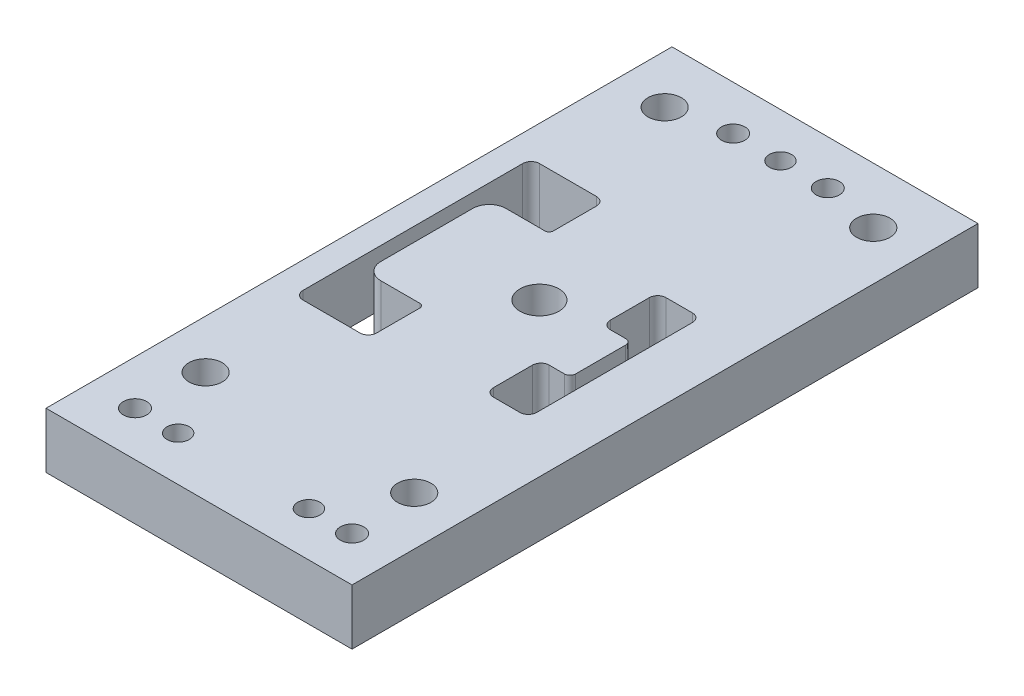
SolidWorks part; units mm, degrees
material "Plain Carbon Steel"
ref_plane "Front Plane" through (0, 0, 0) normal (0, 0, 1) x (1, 0, 0)
ref_plane "Top Plane" through (0, 0, 0) normal (0, 1, 0) x (1, 0, 0)
ref_plane "Right Plane" through (0, 0, 0) normal (1, 0, 0) x (0, 0, -1)
sketch "Sketch1" plane through (0, 0, 0) normal (0, 1, 0) x (1, 0, 0)
  line L1 (-55, -112.5) -> (55, -112.5)
  line L2 (-55, -112.5) -> (-55, 112.5)
  line L3 (-55, 112.5) -> (55, 112.5)
  line L4 (55, -112.5) -> (55, 112.5)
  line L5 (-55, -112.5) -> (55, 112.5) construction
  line L6 (-55, 112.5) -> (55, -112.5) construction
  point P0 (0, 0)
  dimension "D1" = 225
  dimension "D2" = 110
extrude "Boss-Extrude1" add sketch "Sketch1" along normal blind 20
sketch "Sketch2" plane through (0, 20, 0) normal (0, 1, 0) x (1, 0, 0)
  line L0 (-42.5, 37.36) -> (-19, 37.36) construction
  line L1 (-42.5, -17.64) -> (-19, -17.64) construction
  line L8 (-40.5, 26.36) -> (-40.5, -6.64) construction
  line L9 (-42.5, -32.64) -> (-22, -32.64)
  line L11 (-42.5, 52.36) -> (-22, 52.36)
  line L13 (-20.5, 32.36) -> (-34.5, 32.36) construction
  line L14 (-19, 37.36) -> (-19, 33.86) construction
  line L16 (-45.5, 34.36) -> (-45.5, -14.64) construction
  line L18 (-19, -17.64) -> (-19, -14.14) construction
  line L19 (-34.5, -12.64) -> (-20.5, -12.64) construction
  line L20 (-40.5, 26.36) -> (-40.5, -6.64)
  line L21 (-20.5, 32.36) -> (-34.5, 32.36)
  line L22 (-19, 49.36) -> (-19, 33.86)
  line L24 (-45.5, 49.36) -> (-45.5, -29.64)
  line L26 (-19, -29.64) -> (-19, -14.14)
  line L27 (-34.5, -12.64) -> (-20.5, -12.64)
  arc A0 (-22, 52.36) -> (-19, 49.36) centre (-22, 49.36) cw
  arc A1 (-45.5, 49.36) -> (-42.5, 52.36) centre (-42.5, 49.36) cw
  arc A2 (-42.5, -32.64) -> (-45.5, -29.64) centre (-42.5, -29.64) cw
  arc A3 (-22, -32.64) -> (-19, -29.64) centre (-22, -29.64) ccw
  arc A6 (-40.5, -6.64) -> (-34.5, -12.64) centre (-34.5, -6.64) ccw construction
  arc A7 (-34.5, 32.36) -> (-40.5, 26.36) centre (-34.5, 26.36) ccw construction
  arc A8 (-20.5, 32.36) -> (-19, 33.86) centre (-20.5, 33.86) ccw construction
  arc A11 (-19, -14.14) -> (-20.5, -12.64) centre (-20.5, -14.14) ccw construction
  arc A12 (-40.5, -6.64) -> (-34.5, -12.64) centre (-34.5, -6.64) ccw
  arc A13 (-34.5, 32.36) -> (-40.5, 26.36) centre (-34.5, 26.36) ccw
  arc A14 (-20.5, 32.36) -> (-19, 33.86) centre (-20.5, 33.86) ccw
  arc A17 (-19, -14.14) -> (-20.5, -12.64) centre (-20.5, -14.14) ccw
  dimension "D3" = 3
  dimension "D1" = 15
  dimension "D2" = 15
extrude "Cut-Extrude1" cut sketch "Sketch2" against normal up to next
sketch "Sketch3" plane through (0, 20, 0) normal (0, 1, 0) x (1, 0, 0)
  line L0 (22, -8.64) -> (27.5, -8.64) construction
  line L1 (19, -13.64) -> (19, -11.64) construction
  line L3 (34.5, 15.36) -> (34.5, -10.64) construction
  line L5 (19, 18.36) -> (19, 16.36) construction
  line L6 (27.5, 13.36) -> (22, 13.36) construction
  line L7 (29.5, -6.64) -> (29.5, 11.36) construction
  line L8 (22, -8.64) -> (27.5, -8.64)
  line L9 (19, -25.64) -> (19, -11.64)
  line L11 (34.5, 30.36) -> (34.5, -25.64)
  line L13 (19, 30.36) -> (19, 16.36)
  line L14 (27.5, 13.36) -> (22, 13.36)
  line L15 (29.5, -6.64) -> (29.5, 11.36)
  line L16 (22, -28.64) -> (31.5, -28.64)
  line L17 (22, 33.36) -> (31.5, 33.36)
  line L18 (19, 18.36) -> (31.5, 18.36) construction
  line L19 (31.5, -13.64) -> (19, -13.64) construction
  arc A0 (27.5, -8.64) -> (29.5, -6.64) centre (27.5, -6.64) ccw construction
  arc A1 (22, -8.64) -> (19, -11.64) centre (22, -11.64) ccw construction
  arc A4 (19, 16.36) -> (22, 13.36) centre (22, 16.36) ccw construction
  arc A5 (29.5, 11.36) -> (27.5, 13.36) centre (27.5, 11.36) ccw construction
  arc A6 (27.5, -8.64) -> (29.5, -6.64) centre (27.5, -6.64) ccw
  arc A7 (22, -8.64) -> (19, -11.64) centre (22, -11.64) ccw
  arc A10 (19, 16.36) -> (22, 13.36) centre (22, 16.36) ccw
  arc A11 (29.5, 11.36) -> (27.5, 13.36) centre (27.5, 11.36) ccw
  arc A12 (22, 33.36) -> (19, 30.36) centre (22, 30.36) ccw
  arc A13 (31.5, 33.36) -> (34.5, 30.36) centre (31.5, 30.36) cw
  arc A14 (31.5, -28.64) -> (34.5, -25.64) centre (31.5, -25.64) ccw
  arc A15 (22, -28.64) -> (19, -25.64) centre (22, -25.64) cw
  dimension "D3" = 3
  dimension "D1" = 15
  dimension "D2" = 15
extrude "Cut-Extrude2" cut sketch "Sketch3" against normal up to next
sketch "Sketch4" plane through (0, 0, 0) normal (0, -1, 0) x (1, 0, 0)
  circle A0 centre (37.5, 52.64) radius 10.5 construction
  circle A1 centre (12.5, 52.64) radius 10.5 construction
  circle A2 centre (-12.5, 52.64) radius 10.5 construction
  circle A3 centre (-37.5, 52.64) radius 10.5 construction
  circle A4 centre (0, 10.14) radius 10.5 construction
  circle A5 centre (0, -29.86) radius 10.5 construction
  circle A6 centre (37.5, -72.36) radius 10.5 construction
  circle A7 centre (12.5, -72.36) radius 10.5 construction
  circle A8 centre (-12.5, -72.36) radius 10.5 construction
  circle A9 centre (-37.5, -72.36) radius 10.5 construction
  circle A10 centre (37.5, 52.64) radius 10.5
  circle A11 centre (12.5, 52.64) radius 10.5
  circle A12 centre (-12.5, 52.64) radius 10.5
  circle A13 centre (-37.5, 52.64) radius 10.5
  circle A14 centre (0, 10.14) radius 10.5
  circle A15 centre (0, -29.86) radius 10.5
  circle A16 centre (37.5, -72.36) radius 10.5
  circle A17 centre (12.5, -72.36) radius 10.5
  circle A18 centre (-12.5, -72.36) radius 10.5
  circle A19 centre (-37.5, -72.36) radius 10.5
extrude "Cut-Extrude3" cut sketch "Sketch4" against normal blind 14.2
sketch "Sketch5" plane through (0, 20, 0) normal (0, 1, 0) x (1, 0, 0)
  circle A0 centre (-37.5, 92.36) radius 6
  circle A1 centre (37.5, 92.36) radius 6
  circle A2 centre (-37.5, -72.64) radius 6
  circle A3 centre (37.5, -72.64) radius 6
  dimension "D1" = 12
extrude "Cut-Extrude4" cut sketch "Sketch5" against normal up to next
sketch "Sketch6" plane through (0, 20, 0) normal (0, 1, 0) x (1, 0, 0)
  circle A0 centre (0, 9.86) radius 7
  dimension "D1" = 14
extrude "Cut-Extrude5" cut sketch "Sketch6" against normal up to next
hole_wizard "CBORE for M8 Hex Socket Head Cap Screw1" positions "Sketch10" profile "Sketch9" counterbore size "M8" standard "ISO" end condition through all
sketch "Sketch10" plane through (0, 0, 0) normal (0, -1, 0) x (-1, 0, 0)
  line L0 (-55, -112.5) -> (-55, 112.5) construction
  line L1 (55, 112.5) -> (55, -112.5) construction
  line L2 (-55, 112.5) -> (55, 112.5) construction
  line L3 (55, -112.5) -> (-55, -112.5) construction
  point P0 (-17, 96.5)
  point P2 (17, 96.5)
  point P4 (-39, -96.5)
  point P6 (39, -96.5)
  dimension "D1" = 38
  dimension "D2" = 38
  dimension "D3" = 16
  dimension "D4" = 16
  dimension "D5" = 16
  dimension "D6" = 16
sketch "Sketch9" plane through (17, 0, -96.5) normal (1, 0, 0) x (0, 0, -1)
  line L0 (0, 0) -> (0, 20)
  line L1 (0, 20) -> (4.2, 20)
  line L3 (4.2, 20) -> (4.2, 8.6)
  line L4 (4.2, 8.6) -> (7.5, 8.6)
  line L5 (7.5, 8.6) -> (7.5, 0)
  line L7 (7.5, 0) -> (0, 0)
  line L11 (0, -6.35) -> (0, 107.95) construction
  dimension "Thru Hole Dia." = 8.4
  dimension "Thru Hole Depth" = 20
  dimension "C'Bore Dia." = 15
  dimension "C'Bore Depth" = 8.6
hole_wizard "Ø8.0mm Dowel Hole1" positions "Sketch13" profile "Sketch12" hole size "Ø8.0" standard "ISO" end condition through all
sketch "Sketch13" plane through (0, 0, 0) normal (0, -1, 0) x (-1, 0, 0)
  line L0 (-55, 112.5) -> (55, 112.5) construction
  line L1 (55, -112.5) -> (-55, -112.5) construction
  circle A2 centre (-39, -96.5) radius 7.5 construction
  circle A3 centre (39, -96.5) radius 7.5 construction
  point P0 (0, 96.5)
  point P2 (-23.5, -96.5)
  point P4 (23.5, -96.5)
  dimension "D3" = 8
  dimension "D4" = 8
  dimension "D1" = 16
  dimension "D2" = 16
sketch "Sketch12" plane through (0, 0, -96.5) normal (1, 0, 0) x (0, 0, -1)
  line L0 (0, 0) -> (0, 20)
  line L1 (0, 20) -> (4, 20)
  line L2 (4, 20) -> (4, 0)
  line L5 (4, 0) -> (0, 0)
  line L11 (0, -6.35) -> (0, 107.95) construction
  dimension "Thru Hole Dia." = 8
  dimension "Thru Hole Depth" = 20
